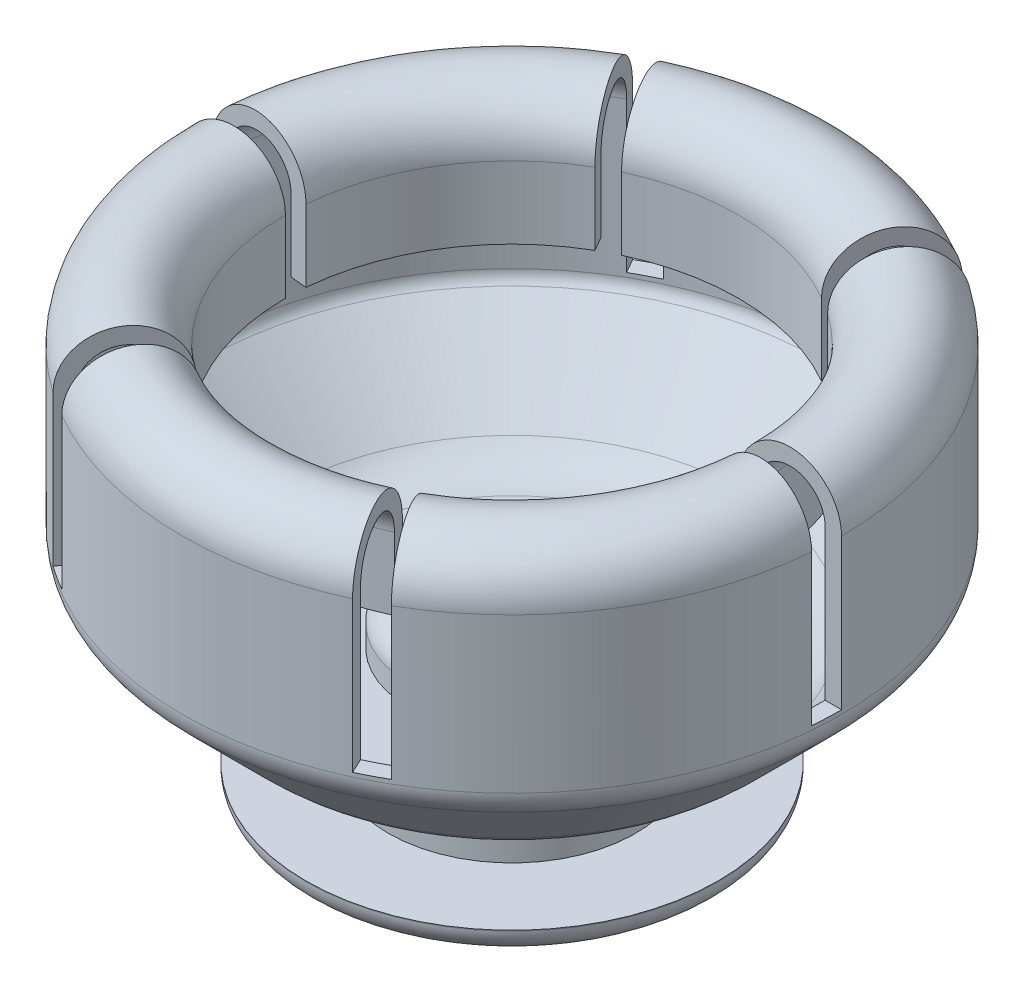
SolidWorks part; units mm, degrees
material "AISI 1020"
ref_plane "Plan de face" through (0, 0, 0) normal (0, 0, 1) x (1, 0, 0)
ref_plane "Plan de dessus" through (0, 0, 0) normal (0, 1, 0) x (1, 0, 0)
ref_plane "Plan de droite" through (0, 0, 0) normal (1, 0, 0) x (0, 0, -1)
sketch "Esquisse1" plane through (0, 0, 0) normal (0, 0, 1) x (1, 0, 0)
  line L0 (0, 1.6458) -> (0, -1.9907) construction
  line L1 (0, 0) -> (0, 0.3)
  line L2 (0, 0.3) -> (0.01, 0.3)
  line L3 (0.16, 0.45) -> (0.16, 0.46)
  line L4 (0.41, 0.71) -> (1.0061, 0.71)
  line L5 (1.2561, 0.46) -> (1.2561, 0.2047)
  line L6 (1.2561, 0.2047) -> (2.2561, 0.2047)
  line L7 (2.8218, 0.439) -> (3.7414, 1.3586)
  line L8 (4, 1.55) -> (3.8, 1.55)
  line L9 (4, 1.55) -> (4, 1.5)
  line L10 (3.8828, 1.2172) -> (2.9586, 0.2929)
  line L11 (2.2515, 0) -> (1.5, 0)
  line L12 (3.8, 1.55) -> (3.8, 1.5)
  line L13 (-2.9949, 0) -> (3.5658, 0) construction
  line L14 (1.5, 0) -> (1.5, -1)
  line L15 (1.5, -1) -> (2.5, -1)
  line L16 (2.5, -1) -> (2.5, -1.01)
  line L17 (2.2, -1.31) -> (0.2, -1.31)
  line L18 (0, 0) -> (0, -1.11)
  arc A0 (1.0061, 0.71) -> (1.2561, 0.46) centre (1.0061, 0.46) cw
  arc A1 (0.16, 0.46) -> (0.41, 0.71) centre (0.41, 0.46) cw
  arc A2 (2.9586, 0.2929) -> (2.2515, 0) centre (2.2515, 1) cw
  arc A3 (2.2561, 0.2047) -> (2.8218, 0.439) centre (2.2561, 1.0047) ccw
  arc A4 (3.7414, 1.3586) -> (3.8, 1.5) centre (3.6, 1.5) ccw
  arc A5 (4, 1.5) -> (3.8828, 1.2172) centre (3.6, 1.5) cw
  arc A6 (0.01, 0.3) -> (0.16, 0.45) centre (0.01, 0.45) ccw
  arc A7 (2.5, -1.01) -> (2.2, -1.31) centre (2.2, -1.01) cw
  arc A8 (0.2, -1.31) -> (0, -1.11) centre (0, -1.31) ccw
  point P23 (2.6657, 0)
  dimension "D3" = 0.25
  dimension "D7" = 1
  dimension "D8" = 0.8
  dimension "D11" = 0.2
  dimension "D12" = 0.4
  dimension "D14" = 0.15
  dimension "D22" = 0.3
  dimension "D23" = 0.4
  dimension "D1" = 0.3
  dimension "D2" = 0.2047
  dimension "D4" = 1.55
  dimension "D5" = 135
  dimension "D6" = 0.2
  dimension "D9" = 4
  dimension "D10" = 0.2
  dimension "D13" = 0.05
  dimension "D15" = 0.01
  dimension "D16" = 0.01
  dimension "D17" = 1
  dimension "D18" = 1
  dimension "D19" = 0.31
  dimension "D20" = 1.5
  dimension "D21" = 2.5
revolve "Révolution1" add sketch "Esquisse1" angle 360 about L0
sketch "Esquisse2" plane through (0, 0, 0) normal (0, 0, 1) x (1, 0, 0)
  line L0 (4, 1.55) -> (4, 3.375)
  line L1 (2.75, 3.375) -> (2.75, 2.5)
  line L2 (3.375, 5.0559) -> (3.375, -0.8191) construction
  line L3 (4, 1.55) -> (3.8, 1.55)
  line L4 (4, 1.55) -> (-4, 1.55) construction
  line L5 (3.8, 1.55) -> (-3.8, 1.55) construction
  line L6 (3.8, 1.55) -> (3.8, 3.375)
  line L7 (2.75, 2.5) -> (2.95, 2.5)
  line L8 (2.95, 2.5) -> (2.95, 3.375)
  line L9 (1.7836, 3.375) -> (4.5797, 3.375) construction
  line L10 (0, -1.5966) -> (0, 6.5478) construction
  arc A0 (3.8, 3.375) -> (2.95, 3.375) centre (3.375, 3.375) ccw
  arc A1 (4, 3.375) -> (2.75, 3.375) centre (3.375, 3.375) ccw
  point P1 (3.375, 3.375)
  dimension "D1" = 0.625
  dimension "D2" = 0.2
  dimension "D3" = 3.375
  dimension "D4" = 0.875
revolve "Révolution2" add sketch "Esquisse2" angle 55 about L10
pattern_circular "Répétition circulaire1" count 6 over 360 about axis through (0, 0, 0) along (0, 1, 0) of "Révolution2"
